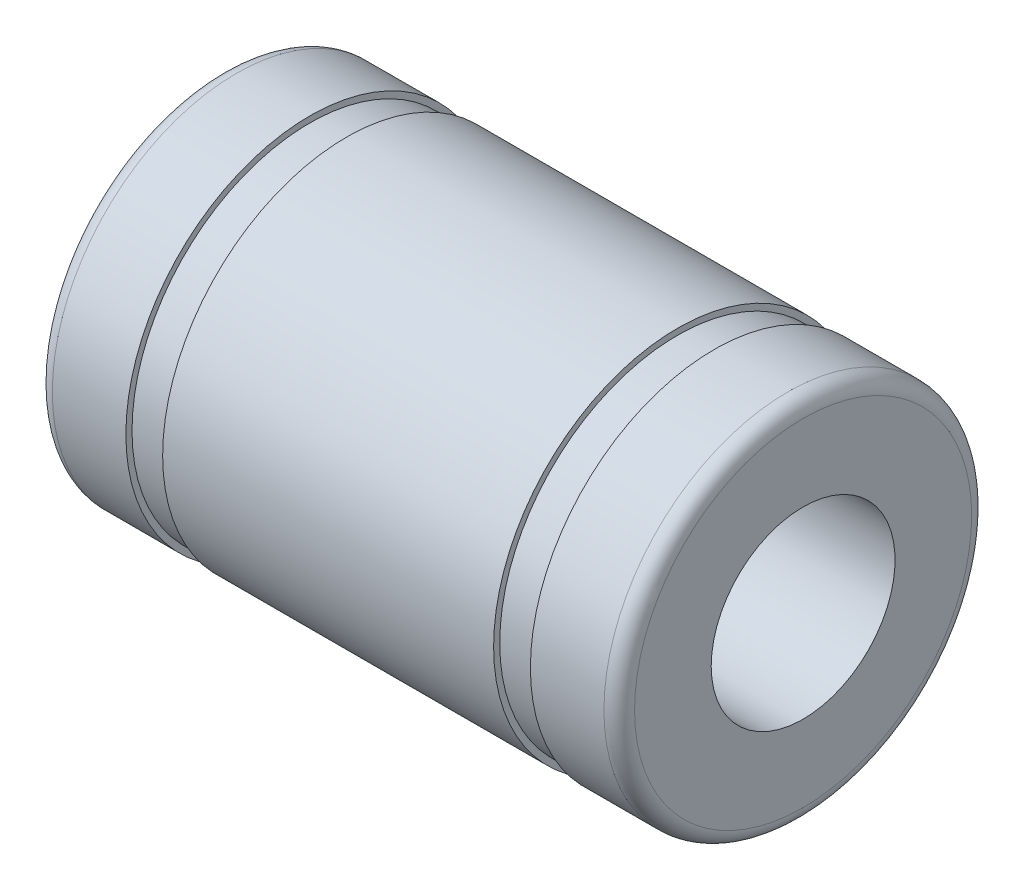
SolidWorks part; units mm, degrees
ref_plane "Front Plane" through (0, 0, 0) normal (0, 0, 1) x (1, 0, 0)
ref_plane "Top Plane" through (0, 0, 0) normal (0, 1, 0) x (1, 0, 0)
ref_plane "Right Plane" through (0, 0, 0) normal (1, 0, 0) x (0, 0, -1)
sketch "Sketch2" plane through (0, 0, 0) normal (0, 1, 0) x (1, 0, 0)
  line L0 (0, 0) -> (11.4368, 0) construction
  line L1 (0, 0) -> (0, 6) construction
  line L2 (-5.4, 6) -> (5.4, 6)
  line L3 (5.4, 6) -> (5.4, 5.8)
  line L4 (5.4, 5.8) -> (6.6, 5.8)
  line L5 (6.6, 5.8) -> (6.6, 6)
  line L6 (6.6, 6) -> (9.5, 6)
  line L7 (9.5, 6) -> (9.5, 3)
  line L8 (9.5, 3) -> (-9.5, 3)
  line L9 (-9.5, 6) -> (-9.5, 3)
  line L10 (-6.6, 6) -> (-9.5, 6)
  line L11 (-6.6, 5.8) -> (-6.6, 6)
  line L12 (-5.4, 5.8) -> (-6.6, 5.8)
  line L13 (-5.4, 6) -> (-5.4, 5.8)
  point P12 (0, 3)
  dimension "D1" = 6
  dimension "D2" = 5.8
  dimension "D3" = 1.2
  dimension "D4" = 6.6
  dimension "D5" = 9.5
  dimension "D6" = 3
revolve "Revolve1" add sketch "Sketch2" angle 360 about L0
fillet "Fillet1" radius 0.5 2 edges at (-9.5, 0, 6) (9.5, 0, 6)
